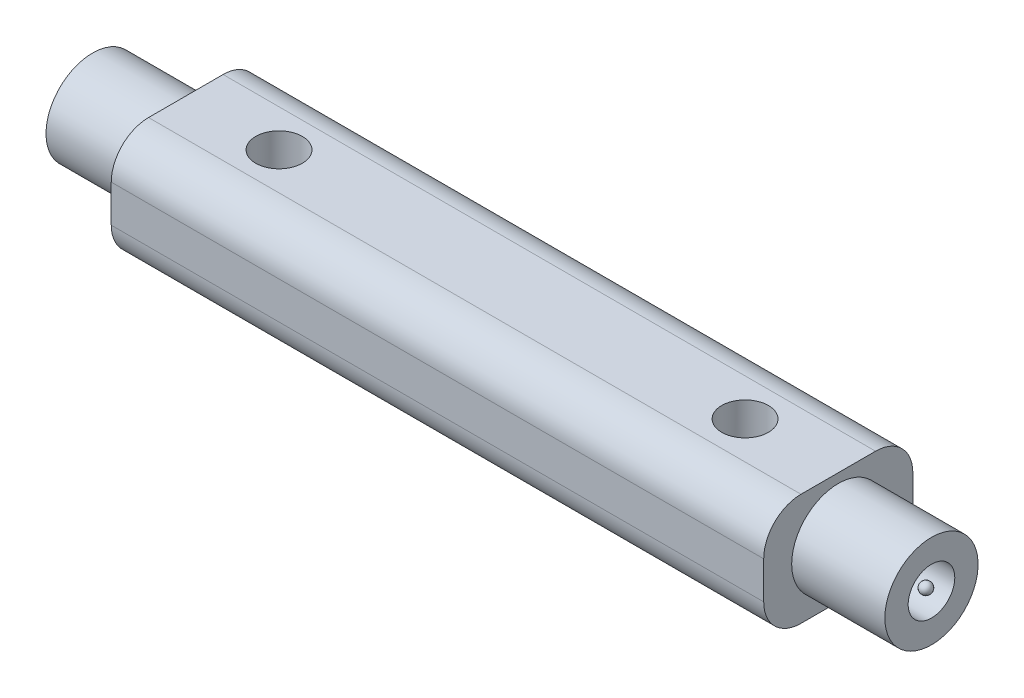
SolidWorks part; units mm, degrees
ref_plane "前基準面" through (0, 0, 0) normal (0, 0, 1) x (1, 0, 0)
ref_plane "上基準面" through (0, 0, 0) normal (0, 1, 0) x (1, 0, 0)
ref_plane "右基準面" through (0, 0, 0) normal (1, 0, 0) x (0, 0, -1)
sketch "草圖1" plane through (0, 0, 0) normal (1, 0, 0) x (0, 0, -1)
  line L0 (4, -3) -> (-4, 3) construction
  line L1 (-4, 3) -> (4, 3)
  line L2 (-4, 3) -> (-4, -3)
  line L3 (-4, -3) -> (4, -3)
  line L4 (4, 3) -> (4, -3)
  dimension "D1" = 6
  dimension "D2" = 8
extrude "填料-伸長1" add sketch "草圖1" along normal mid plane 35
sketch "草圖2" plane through (0, 0, 0) normal (1, 0, 0) x (0, 0, -1)
  circle A0 centre (0, 0) radius 2.5
  dimension "D1" = 5
extrude "填料-伸長2" add sketch "草圖2" along normal mid plane 45
fillet "圓角1" radius 2 4 edges at (0, -3, -4) (0, 3, -4) (0, -3, 4) (0, 3, 4)
hole_wizard "M3 螺紋孔1" positions "草圖4" profile "草圖5" tap size "M3" standard "Iso" end condition through all
sketch "草圖4" plane through (22.5, 0, 0) normal (1, 0, 0) x (0, 0, -1)
  point P0 (0, 0)
sketch "草圖5" plane through (22.5, 0, 0) normal (0, 1, 0) x (0, 0, -1)
  line L0 (0, 0) -> (0, 45)
  line L1 (0, 45) -> (1.25, 45)
  line L2 (1.25, 45) -> (1.25, 0)
  line L5 (1.25, 0) -> (0, 0)
  line L11 (0, -6.35) -> (0, 107.95) construction
  dimension "貫穿螺孔鑽直徑" = 2.5
  dimension "貫穿螺孔鑽深度" = 45
cosmetic thread "鑽孔螺紋1" parameters "D2"=3
sketch "草圖6" plane through (0, 3, 0) normal (0, 1, 0) x (1, 0, 0)
  line L0 (-12.5, 0) -> (12.5, 0) construction
  circle A0 centre (-12.5, 0) radius 1
  circle A1 centre (12.5, 0) radius 1
  dimension "D2" = 2
  dimension "D3" = 2
  dimension "D1" = 25
extrude "除料-伸長1" cut sketch "草圖6" against normal through all
hole_wizard "M3 螺紋孔2" positions "3D草圖1" profile "草圖8" tap size "M3" standard "Iso" end condition through all
sketch3d "3D草圖1"
  line L0 (-12.5, 0.75, 0) -> (-12.5, 3, 0) construction
  line L1 (12.5, 0.75, 0) -> (12.5, 3, 0) construction
  point P0 (-12.5, 3, 0)
  point P4 (12.5, 3, 0)
sketch "草圖8" plane through (-12.5, 3, 0) normal (1, 0, 0) x (0, 0, 1)
  line L0 (0, 0) -> (0, 6)
  line L1 (0, 6) -> (1.25, 6)
  line L2 (1.25, 6) -> (1.25, 0)
  line L5 (1.25, 0) -> (0, 0)
  line L11 (0, -6.35) -> (0, 107.95) construction
  dimension "貫穿螺孔鑽直徑" = 2.5
  dimension "貫穿螺孔鑽深度" = 6
cosmetic thread "鑽孔螺紋2" parameters "D2"=3
cosmetic thread "鑽孔螺紋3" parameters "D2"=3
sketch "草圖10" plane through (0, 0, 0) normal (0, 1, 0) x (1, 0, 0)
  line L0 (-22.5, 0) -> (22.5, 0) construction
  line L1 (-22.5, 2.5) -> (-22.5, -2.5) construction
  line L2 (22.5, -2.5) -> (22.5, 2.5) construction
  line L3 (21.9, 0) -> (22.5, 0)
  line L4 (-22.5, 0) -> (-21.9, 0)
  arc A0 (22.5, 0) -> (21.9, 0) centre (22.2, 0) cw
  arc A1 (-22.5, 0) -> (-21.9, 0) centre (-22.2, 0) cw
  dimension "D1" = 0.3
  dimension "D2" = 0.3
revolve "旋轉1" add sketch "草圖10" angle 360 about L0
